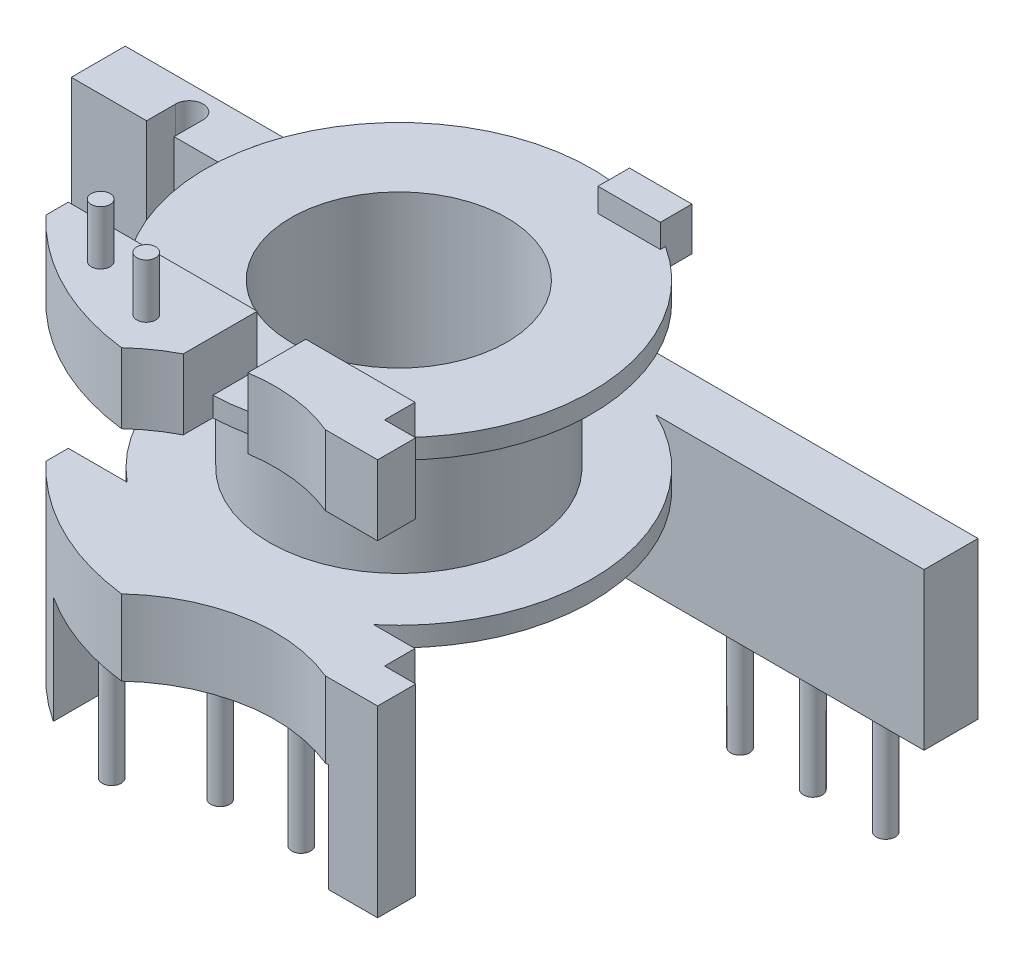
SolidWorks part; units mm, degrees
ref_plane "前视基准面" through (0, 0, 0) normal (0, 0, 1) x (1, 0, 0)
ref_plane "上视基准面" through (0, 0, 0) normal (0, 1, 0) x (1, 0, 0)
ref_plane "右视基准面" through (0, 0, 0) normal (1, 0, 0) x (0, 0, -1)
sketch "草图1" plane through (0, 0, 0) normal (0, 0, 1) x (1, 0, 0)
  line L0 (0, 5.8364) -> (0, -9.3749) construction
  line L2 (4, 0) -> (4, -6.75)
  line L4 (4.8, -0.725) -> (4.8, -6.025)
  line L5 (4.8, -0.725) -> (7.15, -0.725)
  line L7 (4, 0) -> (7.15, 0)
  line L8 (7.15, -0.725) -> (7.15, 0)
  line L9 (4.8, -6.025) -> (7.15, -6.025)
  line L11 (4, -6.75) -> (7.15, -6.75)
  line L12 (7.15, -6.025) -> (7.15, -6.75)
  dimension "D1" = 6.75
  dimension "D2" = 8
  dimension "D3" = 5.3
  dimension "D4" = 0.8
  dimension "D5" = 14.3
revolve "旋转1" add sketch "草图1" angle 360 about L0
sketch "草图2" plane through (0, -0.725, 0) normal (0, 1, 0) x (1, 0, 0)
  line L0 (5.3145, -8.0387) -> (7.2519, -8.0387)
  line L1 (-6.7481, -5.5) -> (0.2519, -5.5)
  line L2 (-6.7481, -5.5) -> (-6.7481, -6.3266)
  line L4 (7.2519, -6.6276) -> (7.2519, -8.0387)
  line L6 (0.2519, -5.5) -> (0.2519, -8.2406)
  line L8 (2.0519, -5.5) -> (2.0519, -7.6497)
  line L13 (2.0519, -5.5) -> (6.0994, -5.5)
  line L16 (6.0994, -5.5) -> (6.0994, -6.6276)
  line L17 (6.0994, -6.6276) -> (7.2519, -6.6276)
  arc A0 (5.3145, -8.0387) -> (2.0519, -7.6497) centre (3, -13.5743) ccw
  arc A1 (-6.7481, -6.3266) -> (-1.0912, -9.1854) centre (0, 0) ccw
  arc A4 (0.2519, -8.2406) -> (-1.0912, -9.1854) centre (3, -13.5743) ccw
  dimension "D1" = 12
  dimension "D2" = 18.5
  dimension "D3" = 3
  dimension "D4" = 7
  dimension "D5" = 1.8
  dimension "D6" = 14
  dimension "D7" = 5.5
extrude "凸台-拉伸1" add sketch "草图2" along normal blind 2.6
sketch "草图3" plane through (0, -0.725, 0) normal (0, 1, 0) x (1, 0, 0)
  line L1 (1.5547, 5.8233) -> (3.8681, 5.8233)
  line L2 (1.5547, 5.8233) -> (1.5547, 6.9922)
  line L3 (1.5547, 6.9922) -> (3.8681, 6.9922)
  line L4 (3.8681, 5.8233) -> (3.8681, 6.9922)
extrude "凸台-拉伸2" add sketch "草图3" along normal blind 1.6
sketch "草图4" plane through (0, -6.025, 0) normal (0, -1, 0) x (1, 0, 0)
  line L2 (-6.7481, 6.3266) -> (-6.7481, 5.5)
  line L3 (-6.7481, 5.5) -> (6.0994, 5.5)
  line L4 (6.0994, 6.6276) -> (6.0994, 5.5)
  line L5 (7.2519, 8.0387) -> (5.3145, 8.0387)
  line L6 (7.2519, 8.0387) -> (7.2519, 6.6276)
  line L7 (7.2519, 6.6276) -> (6.0994, 6.6276)
  line L9 (7.2519, 6.6276) -> (6.0994, 6.6276) construction
  arc A0 (-1.0912, 9.1854) -> (-6.7481, 6.3266) centre (0, 0) ccw
  arc A1 (-1.0912, 9.1854) -> (5.3145, 8.0387) centre (3, 13.5743) ccw
  arc A2 (-1.0912, 9.1854) -> (0.2519, 8.2406) centre (3, 13.5743) ccw construction
extrude "凸台-拉伸3" add sketch "草图4" along normal blind 6.8
sketch "草图5" plane through (0, -12.825, 0) normal (0, -1, 0) x (1, 0, 0)
  line L1 (-5.0607, 9.8679) -> (5.4261, 9.8679)
  line L2 (-5.0607, 9.8679) -> (-5.0607, 5.1262)
  line L3 (-5.0607, 5.1262) -> (5.4261, 5.1262)
  line L4 (5.4261, 9.8679) -> (5.4261, 5.1262)
extrude "切除-拉伸1" cut sketch "草图5" against normal blind 4
sketch "草图6" plane through (0, -8.825, 0) normal (0, -1, 0) x (1, 0, 0)
  circle A0 centre (3.0191, 6.6382) radius 0.35
  circle A1 centre (0.0191, 6.6382) radius 0.35
  circle A2 centre (-2.6672, 7.9737) radius 0.35
  point P6 (0, 6.6477)
  point P7 (3.4321, 6.6477)
  dimension "D1" = 0.7
  dimension "D2" = 3
  dimension "D3" = 3
extrude "凸台-拉伸4" add sketch "草图6" along normal blind 4.5
sketch "草图7" plane through (0, -6.025, 0) normal (0, 1, 0) x (1, 0, 0)
  line L0 (5.3145, -8.0387) -> (7.2519, -8.0387) construction
  line L1 (-18.6, 6.4613) -> (13, 6.4613)
  line L2 (-18.6, 6.4613) -> (-18.6, 8.4613)
  line L3 (-18.6, 8.4613) -> (13, 8.4613)
  line L4 (13, 6.4613) -> (13, 8.4613)
  dimension "D1" = 31.6
  dimension "D2" = 13
  dimension "D3" = 16.5
  dimension "D4" = 2
extrude "凸台-拉伸5" add sketch "草图7" against normal blind 5.8
sketch "草图8" plane through (0, -11.825, 0) normal (0, -1, 0) x (1, 0, 0)
  line L1 (13, -6.4613) -> (13, -8.4613) construction
  circle A0 centre (10.6, -7.4441) radius 0.35
  circle A1 centre (7.9, -7.4441) radius 0.35
  circle A2 centre (5.2, -7.4441) radius 0.35
  point P8 (7.9, -7.4441)
  point P9 (0, 0)
  dimension "D1" = 2.4
  dimension "D2" = 5.4
  dimension "D3" = 2.7
  dimension "D4" = 0.7
extrude "凸台-拉伸6" add sketch "草图8" along normal blind 4.3
sketch "草图9" plane through (0, -11.825, 0) normal (0, -1, 0) x (1, 0, 0)
  line L2 (-18.6, -8.4613) -> (-18.6, -6.4613) construction
  circle A0 centre (-15.3, -7.5388) radius 0.5
  circle A1 centre (-12.5, -7.5388) radius 0.5
  point P4 (0, 0)
  dimension "D1" = 1
  dimension "D2" = 2.8
  dimension "D3" = 3.3
extrude "切除-拉伸2" cut sketch "草图9" against normal blind 14.3
sketch "草图10" plane through (0, 1.875, 0) normal (0, 1, 0) x (1, 0, 0)
  circle A0 centre (-4.2482, -6.7997) radius 0.35
  circle A1 centre (-1.6936, -7.6632) radius 0.35
  point P4 (-4.2482, -6.7997)
  dimension "D1" = 0.7
extrude "凸台-拉伸7" add sketch "草图10" along normal blind 2
sketch "草图11" plane through (0, -6.025, 0) normal (0, 1, 0) x (1, 0, 0)
  line L0 (-15.3, 7.5388) -> (-15.3, 5.8446) construction
  line L1 (-14.7905, 7.5388) -> (-14.7905, 5.8446)
  line L2 (-15.8095, 7.5388) -> (-15.8095, 5.8446)
  line L3 (-12.5, 7.5388) -> (-12.5, 5.6287) construction
  line L4 (-12.02, 7.5388) -> (-12.02, 5.6287)
  line L5 (-12.98, 7.5388) -> (-12.98, 5.6287)
  arc A0 (-14.7905, 7.5388) -> (-15.8095, 7.5388) centre (-15.3, 7.5388) ccw
  arc A1 (-15.8095, 5.8446) -> (-14.7905, 5.8446) centre (-15.3, 5.8446) ccw
  arc A2 (-12.02, 7.5388) -> (-12.98, 7.5388) centre (-12.5, 7.5388) ccw
  arc A3 (-12.98, 5.6287) -> (-12.02, 5.6287) centre (-12.5, 5.6287) ccw
  point P3 (-15.3, 6.6917)
  point P8 (-12.5, 6.5837)
extrude "切除-拉伸3" cut sketch "草图11" against normal blind 4
